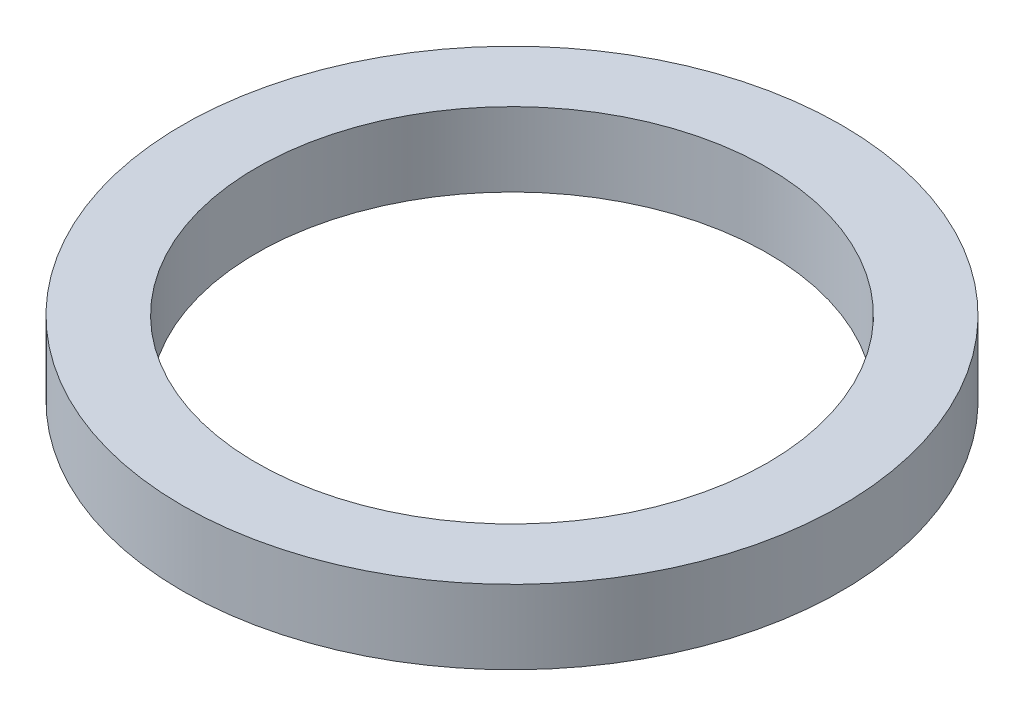
SolidWorks part; units mm, degrees
material "Copper"
ref_plane "Front Plane" through (0, 0, 0) normal (0, 0, 1) x (1, 0, 0)
ref_plane "Top Plane" through (0, 0, 0) normal (0, 1, 0) x (1, 0, 0)
ref_plane "Right Plane" through (0, 0, 0) normal (1, 0, 0) x (0, 0, -1)
sketch "Sketch1" plane through (0, 0, 0) normal (0, 1, 0) x (1, 0, 0)
  circle A0 centre (0, 0) radius 66.908
  dimension "D1" = 133.8161
extrude "Extrude-Thin1" add sketch "Sketch1" along normal blind 15.0165 thin thin type one direction reverse wall 15.0165
